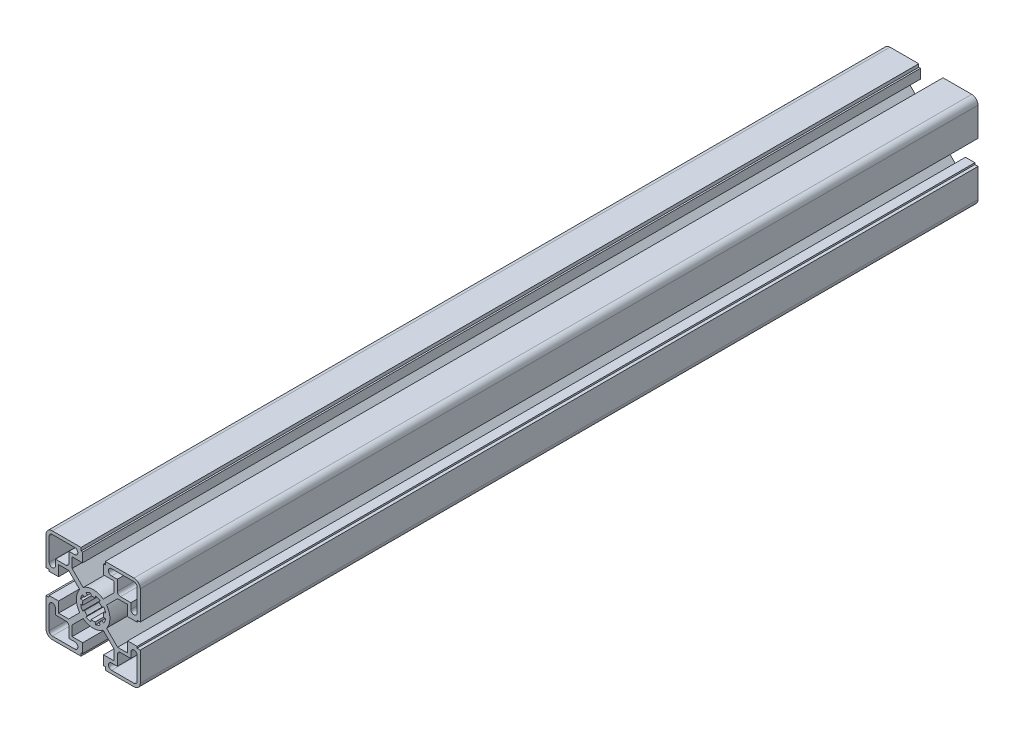
SolidWorks part; units mm, degrees
ref_plane "Front Plane" through (0, 0, 0) normal (0, 0, 1) x (1, 0, 0)
ref_plane "Top Plane" through (0, 0, 0) normal (0, 1, 0) x (1, 0, 0)
ref_plane "Right Plane" through (0, 0, 0) normal (1, 0, 0) x (0, 0, -1)
sketch "Sketch1" plane through (0, 0, 0) normal (0, 0, 1) x (1, 0, 0)
  line L2 (-19.5072, 22.5044) -> (-5.7912, 22.5044)
  line L3 (-5.7912, 22.5044) -> (-5.7912, 21.0058)
  line L4 (-5.7912, 21.0058) -> (-5.0038, 21.0058)
  line L6 (-5.0038, 21.0058) -> (-5.0038, 16.51)
  line L7 (-5.0038, 16.51) -> (-10.0457, 16.51)
  line L8 (-10.0457, 16.51) -> (-10.0457, 11.6801)
  line L9 (-10.0457, 11.6801) -> (-4.781, 6.4154)
  line L11 (-11.6801, 10.0457) -> (-6.4154, 4.781)
  line L12 (-16.51, 10.0457) -> (-11.6801, 10.0457)
  line L13 (-16.51, 5.0038) -> (-16.51, 10.0457)
  line L14 (-21.0058, 5.0038) -> (-16.51, 5.0038)
  line L15 (-21.0058, 5.7912) -> (-21.0058, 5.0038)
  line L16 (-22.5044, 5.7912) -> (-21.0058, 5.7912)
  line L17 (-22.5044, 19.5072) -> (-22.5044, 5.7912)
  line L18 (-18.0086, 11.5443) -> (-13.0429, 11.5443)
  line L19 (-18.0086, 11.5443) -> (-18.0086, 8.7884)
  line L20 (-11.5443, 18.0086) -> (-11.5443, 13.0429)
  line L21 (-21.0058, 19.5072) -> (-21.0058, 8.7884)
  line L23 (-11.5443, 18.0086) -> (-8.7884, 18.0086)
  line L24 (-19.5072, 21.0058) -> (-8.7884, 21.0058)
  line L25 (1.1893, 5.9789) -> (0.9762, 4.9077)
  line L26 (-1.1893, 5.9789) -> (-0.9762, 4.9077)
  line L27 (5.0686, 3.3868) -> (4.1605, 2.78)
  line L28 (3.3868, 5.0686) -> (2.78, 4.1605)
  line L29 (5.9789, -1.1893) -> (4.9077, -0.9762)
  line L30 (5.9789, 1.1893) -> (4.9077, 0.9762)
  line L31 (3.3868, -5.0686) -> (2.78, -4.1605)
  line L32 (5.0686, -3.3868) -> (4.1605, -2.78)
  line L33 (-1.1893, -5.9789) -> (-0.9762, -4.9077)
  line L34 (1.1893, -5.9789) -> (0.9762, -4.9077)
  line L35 (-5.0686, -3.3868) -> (-4.1605, -2.78)
  line L36 (-3.3868, -5.0686) -> (-2.78, -4.1605)
  line L37 (-5.9789, 1.1893) -> (-4.9077, 0.9762)
  line L38 (-5.9789, -1.1893) -> (-4.9077, -0.9762)
  line L39 (-3.3868, 5.0686) -> (-2.78, 4.1605)
  line L40 (-5.0686, 3.3868) -> (-4.1605, 2.78)
  line L41 (11.5443, 18.0086) -> (8.7884, 18.0086)
  line L42 (19.5072, 21.0058) -> (8.7884, 21.0058)
  line L43 (19.5072, 22.5044) -> (5.7912, 22.5044)
  line L44 (5.7912, 22.5044) -> (5.7912, 21.0058)
  line L45 (5.7912, 21.0058) -> (5.0038, 21.0058)
  line L46 (5.0038, 21.0058) -> (5.0038, 16.51)
  line L47 (5.0038, 16.51) -> (10.0457, 16.51)
  line L48 (10.0457, 16.51) -> (10.0457, 11.6801)
  line L49 (10.0457, 11.6801) -> (4.781, 6.4154)
  line L50 (11.6801, 10.0457) -> (6.4154, 4.781)
  line L51 (21.0058, 19.5072) -> (21.0058, 8.7884)
  line L52 (11.5443, 18.0086) -> (11.5443, 13.0429)
  line L53 (18.0086, 11.5443) -> (18.0086, 8.7884)
  line L54 (18.0086, 11.5443) -> (13.0429, 11.5443)
  line L55 (22.5044, 19.5072) -> (22.5044, 5.7912)
  line L56 (22.5044, 5.7912) -> (21.0058, 5.7912)
  line L57 (21.0058, 5.7912) -> (21.0058, 5.0038)
  line L58 (21.0058, 5.0038) -> (16.51, 5.0038)
  line L59 (16.51, 5.0038) -> (16.51, 10.0457)
  line L60 (16.51, 10.0457) -> (11.6801, 10.0457)
  line L61 (16.51, -10.0457) -> (11.6801, -10.0457)
  line L62 (16.51, -5.0038) -> (16.51, -10.0457)
  line L63 (21.0058, -5.0038) -> (16.51, -5.0038)
  line L64 (21.0058, -5.7912) -> (21.0058, -5.0038)
  line L65 (22.5044, -5.7912) -> (21.0058, -5.7912)
  line L66 (22.5044, -19.5072) -> (22.5044, -5.7912)
  line L67 (18.0086, -11.5443) -> (13.0429, -11.5443)
  line L68 (18.0086, -11.5443) -> (18.0086, -8.7884)
  line L69 (11.5443, -18.0086) -> (11.5443, -13.0429)
  line L70 (21.0058, -19.5072) -> (21.0058, -8.7884)
  line L71 (11.6801, -10.0457) -> (6.4154, -4.781)
  line L72 (10.0457, -11.6801) -> (4.781, -6.4154)
  line L73 (10.0457, -16.51) -> (10.0457, -11.6801)
  line L74 (5.0038, -16.51) -> (10.0457, -16.51)
  line L75 (5.0038, -21.0058) -> (5.0038, -16.51)
  line L76 (5.7912, -21.0058) -> (5.0038, -21.0058)
  line L77 (5.7912, -22.5044) -> (5.7912, -21.0058)
  line L78 (19.5072, -22.5044) -> (5.7912, -22.5044)
  line L79 (19.5072, -21.0058) -> (8.7884, -21.0058)
  line L80 (11.5443, -18.0086) -> (8.7884, -18.0086)
  line L81 (-11.5443, -18.0086) -> (-8.7884, -18.0086)
  line L82 (-19.5072, -21.0058) -> (-8.7884, -21.0058)
  line L83 (-19.5072, -22.5044) -> (-5.7912, -22.5044)
  line L84 (-5.7912, -22.5044) -> (-5.7912, -21.0058)
  line L85 (-5.7912, -21.0058) -> (-5.0038, -21.0058)
  line L86 (-5.0038, -21.0058) -> (-5.0038, -16.51)
  line L87 (-5.0038, -16.51) -> (-10.0457, -16.51)
  line L88 (-10.0457, -16.51) -> (-10.0457, -11.6801)
  line L89 (-10.0457, -11.6801) -> (-4.781, -6.4154)
  line L90 (-11.6801, -10.0457) -> (-6.4154, -4.781)
  line L91 (-21.0058, -19.5072) -> (-21.0058, -8.7884)
  line L92 (-11.5443, -18.0086) -> (-11.5443, -13.0429)
  line L93 (-18.0086, -11.5443) -> (-18.0086, -8.7884)
  line L94 (-18.0086, -11.5443) -> (-13.0429, -11.5443)
  line L95 (-22.5044, -19.5072) -> (-22.5044, -5.7912)
  line L96 (-22.5044, -5.7912) -> (-21.0058, -5.7912)
  line L97 (-21.0058, -5.7912) -> (-21.0058, -5.0038)
  line L98 (-21.0058, -5.0038) -> (-16.51, -5.0038)
  line L99 (-16.51, -5.0038) -> (-16.51, -10.0457)
  line L100 (-16.51, -10.0457) -> (-11.6801, -10.0457)
  arc A0 (-22.5044, 19.5072) -> (-19.5072, 22.5044) centre (-19.5072, 19.5072) cw
  arc A1 (-21.0058, 8.7884) -> (-18.0086, 8.7884) centre (-19.5072, 8.7884) ccw
  arc A2 (-21.0058, 19.5072) -> (-19.5072, 21.0058) centre (-19.5072, 19.5072) cw
  arc A3 (-8.7884, 21.0058) -> (-8.7884, 18.0086) centre (-8.7884, 19.5072) cw
  arc A4 (-11.5443, 13.0429) -> (-13.0429, 11.5443) centre (-13.0429, 13.0429) cw
  arc A5 (6.4154, -4.781) -> (6.4154, 4.781) centre (0, 0) ccw
  arc A6 (0.9762, 4.9077) -> (-0.9762, 4.9077) centre (0, 0) ccw
  arc A7 (-5.0686, 3.3868) -> (-5.9789, 1.1893) centre (0, 0) ccw
  arc A8 (4.1605, 2.78) -> (2.78, 4.1605) centre (0, 0) ccw
  arc A9 (4.9077, -0.9762) -> (4.9077, 0.9762) centre (0, 0) ccw
  arc A10 (2.78, -4.1605) -> (4.1605, -2.78) centre (0, 0) ccw
  arc A11 (-0.9762, -4.9077) -> (0.9762, -4.9077) centre (0, 0) ccw
  arc A12 (-4.1605, -2.78) -> (-2.78, -4.1605) centre (0, 0) ccw
  arc A13 (-4.9077, 0.9762) -> (-4.9077, -0.9762) centre (0, 0) ccw
  arc A14 (-2.78, 4.1605) -> (-4.1605, 2.78) centre (0, 0) ccw
  arc A15 (-5.9789, -1.1893) -> (-5.0686, -3.3868) centre (0, 0) ccw
  arc A16 (-3.3868, -5.0686) -> (-1.1893, -5.9789) centre (0, 0) ccw
  arc A17 (1.1893, -5.9789) -> (3.3868, -5.0686) centre (0, 0) ccw
  arc A18 (5.0686, -3.3868) -> (5.9789, -1.1893) centre (0, 0) ccw
  arc A19 (5.9789, 1.1893) -> (5.0686, 3.3868) centre (0, 0) ccw
  arc A20 (3.3868, 5.0686) -> (1.1893, 5.9789) centre (0, 0) ccw
  arc A21 (-1.1893, 5.9789) -> (-3.3868, 5.0686) centre (0, 0) ccw
  arc A22 (8.7884, 21.0058) -> (8.7884, 18.0086) centre (8.7884, 19.5072) ccw
  arc A23 (21.0058, 19.5072) -> (19.5072, 21.0058) centre (19.5072, 19.5072) ccw
  arc A24 (22.5044, 19.5072) -> (19.5072, 22.5044) centre (19.5072, 19.5072) ccw
  arc A25 (11.5443, 13.0429) -> (13.0429, 11.5443) centre (13.0429, 13.0429) ccw
  arc A26 (21.0058, 8.7884) -> (18.0086, 8.7884) centre (19.5072, 8.7884) cw
  arc A27 (21.0058, -8.7884) -> (18.0086, -8.7884) centre (19.5072, -8.7884) ccw
  arc A28 (11.5443, -13.0429) -> (13.0429, -11.5443) centre (13.0429, -13.0429) cw
  arc A29 (22.5044, -19.5072) -> (19.5072, -22.5044) centre (19.5072, -19.5072) cw
  arc A30 (21.0058, -19.5072) -> (19.5072, -21.0058) centre (19.5072, -19.5072) cw
  arc A31 (8.7884, -21.0058) -> (8.7884, -18.0086) centre (8.7884, -19.5072) cw
  arc A32 (-8.7884, -21.0058) -> (-8.7884, -18.0086) centre (-8.7884, -19.5072) ccw
  arc A33 (-21.0058, -19.5072) -> (-19.5072, -21.0058) centre (-19.5072, -19.5072) ccw
  arc A34 (-22.5044, -19.5072) -> (-19.5072, -22.5044) centre (-19.5072, -19.5072) ccw
  arc A35 (-11.5443, -13.0429) -> (-13.0429, -11.5443) centre (-13.0429, -13.0429) ccw
  arc A36 (-21.0058, -8.7884) -> (-18.0086, -8.7884) centre (-19.5072, -8.7884) cw
  arc A37 (4.781, 6.4154) -> (-4.781, 6.4154) centre (0, 0) ccw
  arc A38 (-4.781, -6.4154) -> (4.781, -6.4154) centre (0, 0) ccw
  arc A39 (-6.4154, 4.781) -> (-6.4154, -4.781) centre (0, 0) ccw
extrude "Boss-Extrude1" add sketch "Sketch1" along normal mid plane 400
